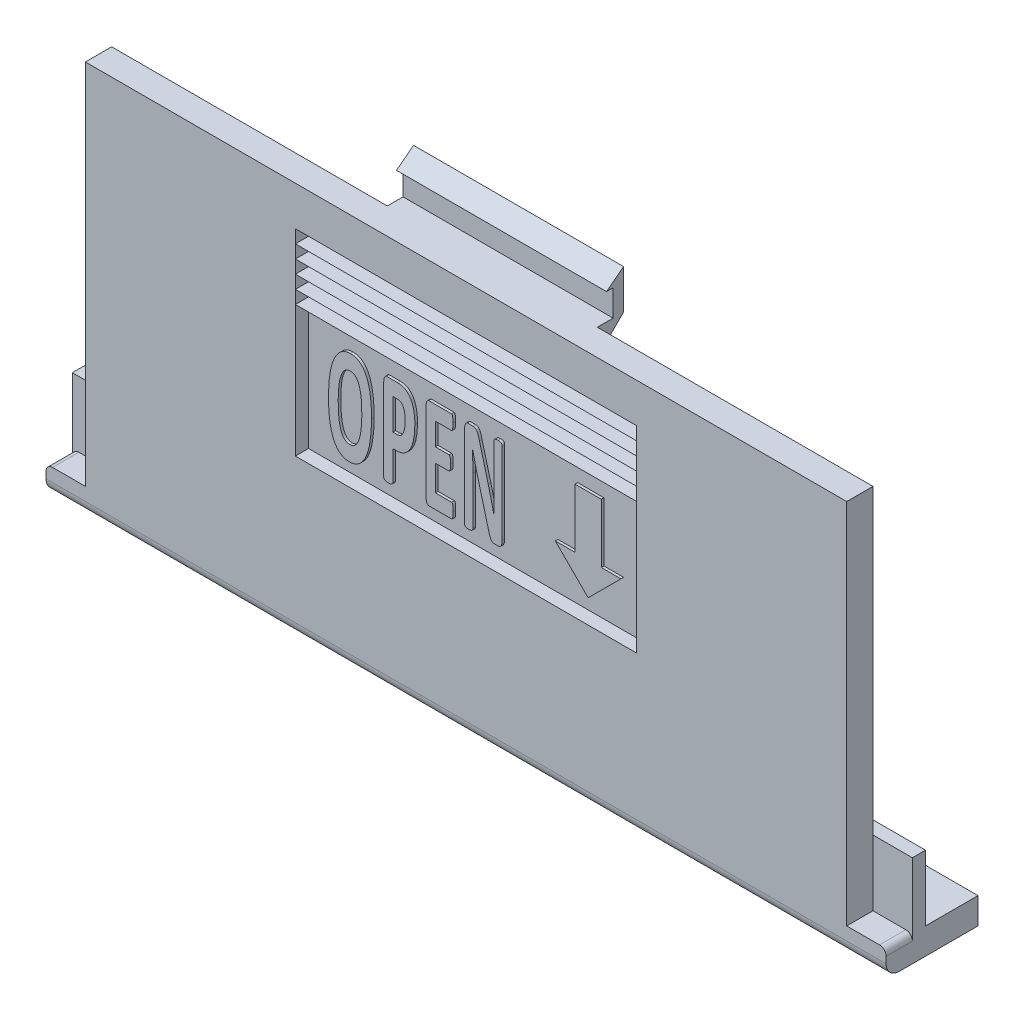
SolidWorks part; units mm, degrees
material "ABS PC"
ref_plane "Piano frontale" through (0, 0, 0) normal (0, 0, 1) x (1, 0, 0)
ref_plane "Piano superiore" through (0, 0, 0) normal (0, 1, 0) x (1, 0, 0)
ref_plane "Piano destro" through (0, 0, 0) normal (1, 0, 0) x (0, 0, -1)
sketch "Schizzo1" plane through (0, 0, 0) normal (0, 0, 1) x (1, 0, 0)
  line L1 (-32, 15) -> (32, 15)
  line L2 (-32, 15) -> (-32, -15)
  line L3 (-32, -15) -> (32, -15)
  line L4 (32, 15) -> (32, -15)
  line L5 (-32, 15) -> (32, -15) construction
  line L6 (-32, -15) -> (32, 15) construction
  point P0 (0, 0)
  dimension "D1" = 64
  dimension "D2" = 30
extrude "Estrusione-Faccia sportello" add sketch "Schizzo1" along normal mid plane 2
sketch "Schizzo3" plane through (0, 0, 0) normal (0, 0, 1) x (1, 0, 0)
  line L0 (-29, 15) -> (-29, -13)
  line L1 (32, 15) -> (-32, 15) construction
  line L2 (-29, -13) -> (-32, -13)
  line L3 (-32, 15) -> (-32, -15) construction
  line L4 (-32, -13) -> (-32, 15)
  line L5 (-32, 15) -> (-29, 15)
  line L6 (-32, -15) -> (32, -15) construction
  dimension "D1" = 2
  dimension "D2" = 3
extrude "Taglio-Estrusione3" cut sketch "Schizzo3" against normal blind 2 and the other way blind 2
sketch "Schizzo4" plane through (0, 0, 0) normal (0, 0, 1) x (1, 0, 0)
  line L0 (-32, -15) -> (32, -15) construction
  line L1 (32, 15) -> (29, 15)
  line L2 (32, 15) -> (32, -13)
  line L3 (32, -13) -> (29, -13)
  line L4 (29, 15) -> (29, -13)
  dimension "D1" = 2
  dimension "D2" = 3
extrude "Taglio-Estrusione4" cut sketch "Schizzo4" against normal blind 2 and the other way blind 2
sketch "Schizzo5" plane through (0, 0, 0) normal (1, 0, 0) x (0, 0, -1)
  line L0 (0, -14.5) -> (8.6664, -14.5) construction
  line L12 (1, -15) -> (6, -15)
  line L13 (1, -15) -> (1, -13)
  line L14 (1, -13) -> (6, -13)
  line L15 (6, -15) -> (6, -13)
  line L16 (1, -13) -> (1, 15) construction
  dimension "D1" = 5
  dimension "D2" = 2
extrude "Estrusione-Chiusura inferiore sportello" add sketch "Schizzo5" along normal up to vertex (32 mm away) and the other way up to vertex (32 mm away) up to point (32, -15, -1) other way up to point (-32, -15, -1)
ref_plane "Piano alette sportello" through (28, 0, 0) normal (1, 0, 0) x (0, 0, -1)
sketch "Schizzo7" plane through (28, 0, 0) normal (1, 0, 0) x (0, 0, -1)
  line L2 (2, -13) -> (2, -8)
  line L3 (2, -8) -> (1, -8)
  line L4 (1, -13) -> (1, 15) construction
  line L5 (1, -8) -> (1, -13)
  line L8 (1, -13) -> (2, -13)
  line L9 (1, -13) -> (1, 15) construction
  dimension "D1" = 1
  dimension "D2" = 5
extrude "Estrusione-Aletta sportello inferiore" add sketch "Schizzo7" along normal up to vertex (4 mm away)
ref_plane "Piano5" through (-28, 0, 0) normal (1, 0, 0) x (0, 0, -1)
sketch "Schizzo24" plane through (-28, 0, 0) normal (1, 0, 0) x (0, 0, -1)
  line L0 (2, -13) -> (2, -8)
  line L1 (2, -8) -> (1, -8)
  line L2 (1, -8) -> (1, -13)
  line L3 (1, -13) -> (2, -13)
  line L4 (1, 15) -> (1, -13) construction
  dimension "D1" = 5
  dimension "D2" = 1
extrude "Estrusione-Estrusione12" add sketch "Schizzo24" against normal up to vertex (4 mm away)
sketch "Schizzo8" plane through (0, 0, 0) normal (1, 0, 0) x (0, 0, -1)
  line L0 (1, 15) -> (1, 13)
  line L1 (1, -8) -> (1, 15) construction
  line L2 (1, 13) -> (3, 15)
  line L3 (3, 15) -> (1, 15)
  line L4 (1, -8) -> (1, -13) construction
  dimension "D1" = 2
  dimension "D2" = 2
extrude "Estrusione-Supporto chiusura " add sketch "Schizzo8" along normal blind 8 and the other way blind 8
sketch "Schizzo9" plane through (0, 0, 0) normal (1, 0, 0) x (0, 0, -1)
  line L0 (2.2, 15) -> (3, 15)
  line L2 (3, 15) -> (3, 18)
  line L3 (3, 18) -> (1.7, 17)
  line L4 (2.2, 15) -> (2.2, 17)
  line L5 (2.2, 17) -> (1.7, 17)
  line L6 (-1, 15) -> (1, 15) construction
  line L7 (-1, 15) -> (1, 15) construction
  dimension "D1" = 3
  dimension "D2" = 0.5
  dimension "D3" = 2
  dimension "D4" = 0.8
extrude "Estrusione-Gancio chiusura" add sketch "Schizzo9" along normal blind 8 and the other way blind 8
sketch "Schizzo10" plane through (0, 0, 0) normal (0, 0, 1) x (1, 0, 0)
  line L0 (0, 0) -> (0, 18) construction
  line L1 (-8, 18) -> (8, 18) construction
  line L2 (29, 15) -> (-29, 15) construction
  line L3 (-13, 12) -> (13, 12)
  line L4 (-13, 12) -> (-13, -3)
  line L5 (-13, -3) -> (13, -3)
  line L6 (13, 12) -> (13, -3)
  line L7 (-29, 15) -> (-29, -13) construction
  line L8 (29, -13) -> (29, 15) construction
  dimension "D1" = 3
  dimension "D2" = 15
  dimension "D3" = 16
  dimension "D4" = 16
extrude "Taglio-Scavo sportello" cut sketch "Schizzo10" along normal blind 1
ref_plane "Piano3" through (-13, 0, 0) normal (1, 0, 0) x (0, 0, -1)
sketch "Schizzo13" plane through (-13, 0, 0) normal (1, 0, 0) x (0, 0, -1)
  line L0 (-1, 12) -> (0, 12)
  line L1 (-1, 12) -> (0, 12) construction
  line L2 (0, 12) -> (0, 11)
  line L3 (0, 11) -> (-1, 12)
  dimension "D1" = 1
extrude "Estrusione-Estrusione7" add sketch "Schizzo13" along normal up to surface (26 mm away) up to face at (13, 4.5, 0.5)
sketch "Schizzo14" plane through (-13, 0, 0) normal (1, 0, 0) x (0, 0, -1)
  line L0 (0, 11) -> (-1, 11)
  line L1 (-1, 12) -> (-1, -3) construction
  line L2 (-1, 11) -> (0, 10)
  line L3 (0, 11) -> (0, -3) construction
  line L4 (0, 10) -> (0, 11)
  dimension "D1" = 1
extrude "Estrusione-Estrusione8" add sketch "Schizzo14" along normal up to surface (26 mm away) up to face at (13, 4.25, 0.5)
ref_plane "Piano4" through (0, 12, 0) normal (0, 1, 0) x (1, 0, 0)
pattern_linear "Ripetizione a L3" count 5 spacing 1 along (0, -1, 0) of "Estrusione-Estrusione8"
sketch "Guida testo" plane through (0, 0, 0) normal (0, 0, 1) x (1, 0, 0)
  line L0 (-13, -2) -> (13, -2) construction
  line L3 (-13, 6) -> (-13, -3) construction
  line L4 (13, -3) -> (13, 6) construction
  line L5 (-13, -3) -> (13, -3) construction
  line L7 (-13, 5) -> (13, 5) construction
  line L8 (-13, 7) -> (-13, -3) construction
  line L9 (13, -3) -> (13, 7) construction
  line L10 (13, 6) -> (-13, 6) construction
  line L11 (-12, 5) -> (-12, -2) construction
  line L12 (11, 5) -> (11, -2) construction
  dimension "D1" = 1
  dimension "D2" = 1
  dimension "D3" = 1
  dimension "D4" = 2
sketch "Schizzo19" plane through (0, 0, 0) normal (0, 0, 1) x (1, 0, 0)
  text T0 "<b> OPEN</b>" font "Calibri" height 7
extrude "Estrusione-Open" add sketch "Schizzo19" along normal blind 0.2
sketch "Schizzo22" plane through (0, 0, 0) normal (0, 0, 1) x (1, 0, 0)
  line L0 (8.5, -2) -> (8.5, 5) construction
  line L1 (-13, -2) -> (13, -2) construction
  line L2 (-13, 5) -> (13, 5) construction
  line L3 (11, 5) -> (11, -2) construction
  line L4 (8.5, -2) -> (11, 0.5)
  line L5 (11, 0.5) -> (9.5, 0.5)
  line L6 (9.5, 0.5) -> (9.5, 5)
  line L7 (9.5, 5) -> (8.5, 5)
  line L8 (8.5, 5) -> (7.5, 5)
  line L9 (7.5, 5) -> (7.5, 0.5)
  line L10 (7.5, 0.5) -> (6, 0.5)
  line L11 (6, 0.5) -> (8.5, -2)
  dimension "D1" = 2.5
  dimension "D2" = 2
  dimension "D3" = 2
  dimension "D4" = 45
  dimension "D5" = 45
  dimension "D6" = 1.5
extrude "Estrusione-Estrusione11" add sketch "Schizzo22" along normal blind 0.2
fillet "Raccordo6" radius 0.5 1 edges at (-32, -13, 0)
fillet "Raccordo7" radius 0.5 1 edges at (32, -13, 0)
fillet "Raccordo10" radius 0.5 1 edges at (0, 13, -1)
fillet "Raccordo11" radius 1 1 edges at (0, -15, 1)
